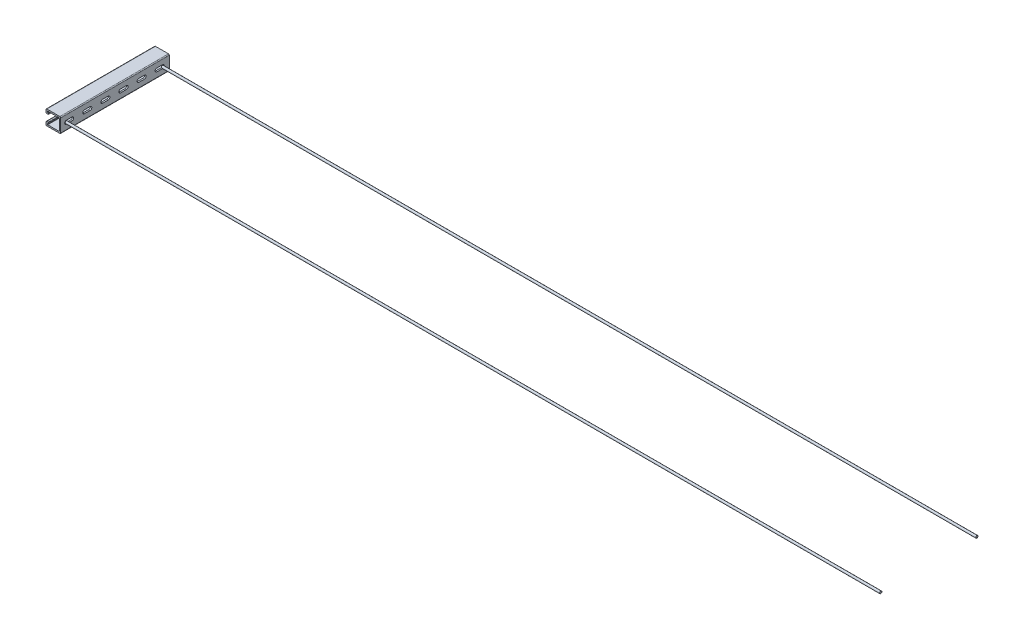
SolidWorks part; units mm, degrees
ref_plane "Front Plane" through (0, 0, 0) normal (0, 0, 1) x (1, 0, 0)
ref_plane "Top Plane" through (0, 0, 0) normal (0, 1, 0) x (1, 0, 0)
ref_plane "Right Plane" through (0, 0, 0) normal (1, 0, 0) x (0, 0, -1)
sketch "Sketch1" plane through (0, 0, 0) normal (0, 0, 1) x (1, 0, 0)
  line L0 (-13.5255, 9.525) -> (-18.2499, 9.525)
  line L1 (-20.6375, 11.9126) -> (-20.6375, 18.2499)
  line L2 (-18.2499, 20.6375) -> (18.2499, 20.6375)
  line L3 (20.6375, 18.2499) -> (20.6375, -18.2499)
  line L4 (18.2499, -20.6375) -> (-18.2499, -20.6375)
  line L5 (-20.6375, -18.2499) -> (-20.6375, -11.9126)
  line L6 (-18.2499, -9.525) -> (-13.5255, -9.525)
  line L7 (0, 0) -> (20.6375, 0) construction
  line L8 (0, 0) -> (0, 20.6375) construction
  arc A0 (-20.6375, 18.2499) -> (-18.2499, 20.6375) centre (-18.2499, 18.2499) cw
  arc A1 (-18.2499, 9.525) -> (-20.6375, 11.9126) centre (-18.2499, 11.9126) cw
  arc A2 (-20.6375, -11.9126) -> (-18.2499, -9.525) centre (-18.2499, -11.9126) cw
  arc A3 (-18.2499, -20.6375) -> (-20.6375, -18.2499) centre (-18.2499, -18.2499) cw
  arc A4 (20.6375, -18.2499) -> (18.2499, -20.6375) centre (18.2499, -18.2499) cw
  arc A5 (18.2499, 20.6375) -> (20.6375, 18.2499) centre (18.2499, 18.2499) cw
  point P14 (-20.6375, 20.6375)
  point P23 (20.6375, -20.6375)
  point P26 (20.6375, 20.6375)
  dimension "D4" = 2.3876
  dimension "D1" = 41.275
  dimension "D2" = 41.275
  dimension "D3" = 19.05
  dimension "D5" = 7.112
extrude "Extrude-Thin1" add sketch "Sketch1" against normal blind 304.8 thin
fillet "Fillet2" radius 0.762 8 edges at (-16.5735, 13.589, -152.4) (-16.5735, -16.5735, -152.4) (-16.5735, 16.5735, -152.4) (-13.5255, 13.589, -152.4) (-13.5255, 9.525, -152.4) (-13.5255, -9.525, -152.4) (-13.5255, -13.589, -152.4) (-16.5735, -13.589, -152.4)
fillet "Fillet3" radius 1.524 2 edges at (16.5735, 16.5735, -152.4) (16.5735, -16.5735, -152.4)
sketch "Sketch2" plane through (20.6375, 0, 0) normal (1, 0, 0) x (0, 0, -1)
  line L0 (15.875, 0) -> (31.75, 0) construction
  line L1 (15.875, 4.7625) -> (31.75, 4.7625)
  line L2 (15.875, -4.7625) -> (31.75, -4.7625)
  line L4 (15.875, 0) -> (0, 0) construction
  line L5 (23.8125, 0) -> (74.6125, 0) construction
  line L6 (0, 18.2499) -> (0, -18.2499) construction
  arc A0 (15.875, 4.7625) -> (15.875, -4.7625) centre (15.875, 0) ccw
  arc A1 (31.75, -4.7625) -> (31.75, 4.7625) centre (31.75, 0) ccw
  point P2 (23.8125, 0)
  dimension "D1" = 9.525
  dimension "D2" = 25.4
  dimension "Center Length" = 50.8
  dimension "D3" = 11.1125
extrude "Cut-Extrude1" cut sketch "Sketch2" against normal through all
pattern_linear "LPattern1" count 6 spacing 50.8 along (0, 0, -1) of "Cut-Extrude1"
sketch "Sketch3" plane through (0, 0, 0) normal (1, 0, 0) x (0, 0, -1)
  line L0 (0, 0) -> (304.8, 0) construction
  line L1 (304.8, 18.2499) -> (304.8, -18.2499) construction
  point P3 (101.6, 0)
  point P4 (203.2, 0)
  dimension "D1" = 101.6
  dimension "D2" = 101.6
sketch "Sketch4" plane through (20.6375, 0, 0) normal (1, 0, 0) x (0, 0, -1)
  circle A0 centre (15.875, 0) radius 3.175
  circle A1 centre (285.75, 0) radius 3.175
  dimension "D1" = 6.35
extrude "Boss-Extrude1" add sketch "Sketch4" along normal blind 2286 separate body
equation "\"D3@LPattern1\" = \"Center Length@Sketch2\""
equation "\"D1@LPattern1\" = \"Length@Extrude-Thin1\"/\"Center Length@Sketch2\""
